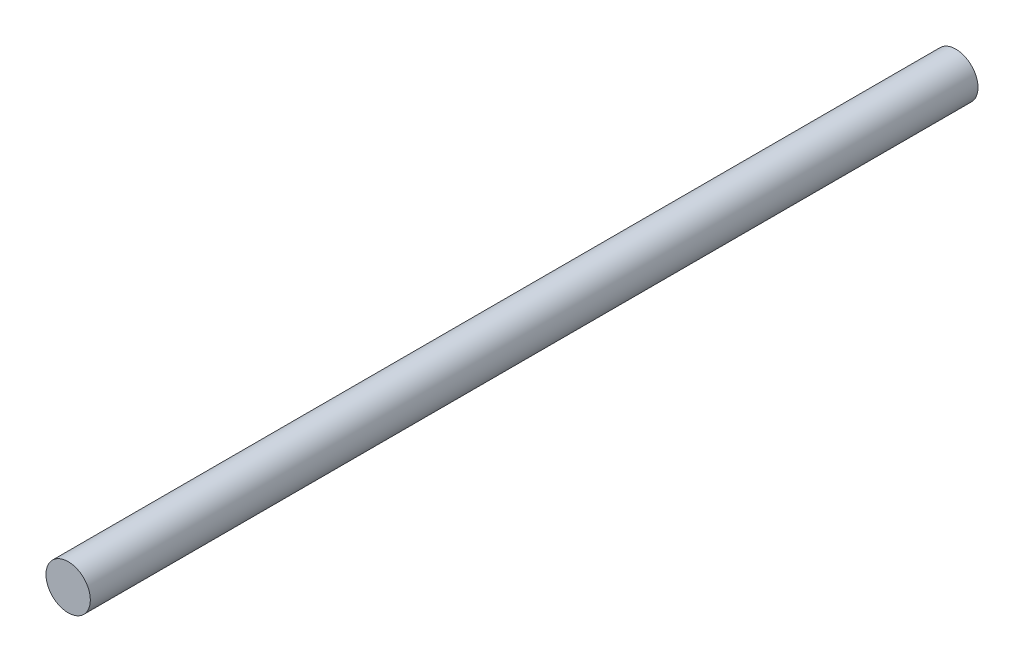
SolidWorks part; units mm, degrees
material "AISI 304"
ref_plane "前视基准面" through (0, 0, 0) normal (0, 0, 1) x (1, 0, 0)
ref_plane "上视基准面" through (0, 0, 0) normal (0, 1, 0) x (1, 0, 0)
ref_plane "右视基准面" through (0, 0, 0) normal (1, 0, 0) x (0, 0, -1)
sketch "草图1" plane through (0, 0, 0) normal (0, 0, 1) x (1, 0, 0)
  circle A0 centre (0, 0) radius 0.5
  dimension "D1" = 1
extrude "凸台-拉伸1" add sketch "草图1" along normal blind 20
